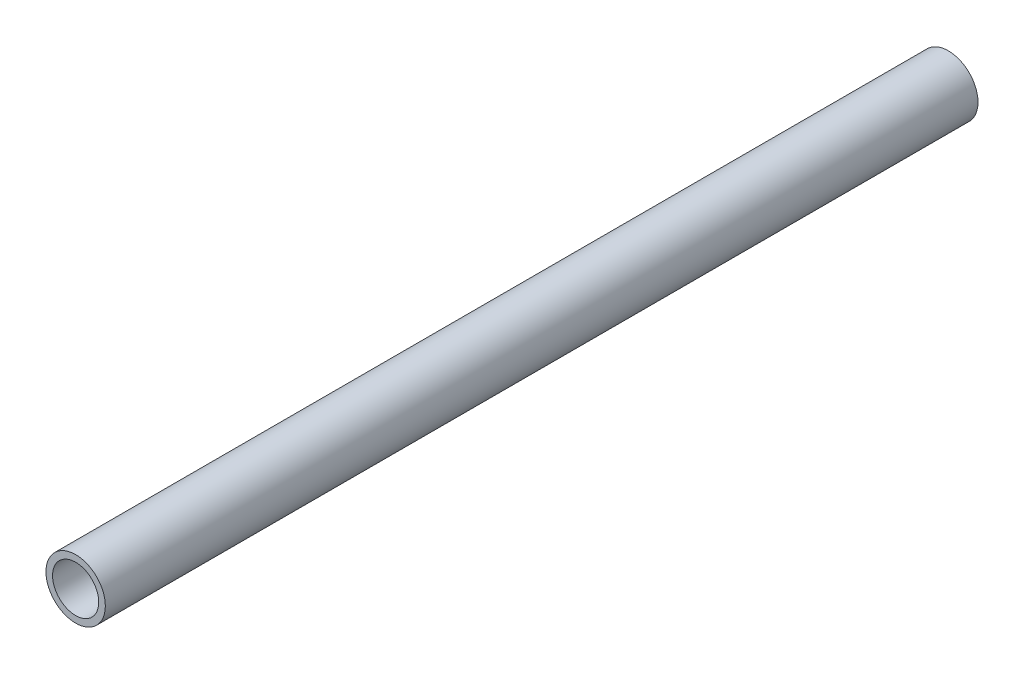
SolidWorks part; units mm, degrees
ref_plane "Front Plane" through (0, 0, 0) normal (0, 0, 1) x (1, 0, 0)
ref_plane "Top Plane" through (0, 0, 0) normal (0, 1, 0) x (1, 0, 0)
ref_plane "Right Plane" through (0, 0, 0) normal (1, 0, 0) x (0, 0, -1)
sketch "Sketch1" plane through (0, 0, 0) normal (0, 0, 1) x (1, 0, 0)
  circle A0 centre (0, 0) radius 9
  circle A1 centre (0, 0) radius 7
  dimension "D1" = 14
  dimension "D2" = 18
extrude "Boss-Extrude1" add sketch "Sketch1" along normal blind 264.45
